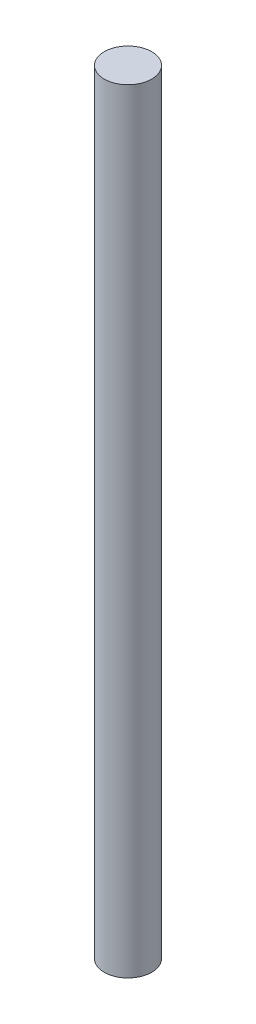
SolidWorks part; units mm, degrees
ref_plane "Front Plane" through (0, 0, 0) normal (0, 0, 1) x (1, 0, 0)
ref_plane "Top Plane" through (0, 0, 0) normal (0, 1, 0) x (1, 0, 0)
ref_plane "Right Plane" through (0, 0, 0) normal (1, 0, 0) x (0, 0, -1)
sketch "Sketch1" plane through (0, 0, 0) normal (0, 0, 1) x (1, 0, 0)
  line L0 (0, 0) -> (0, 220)
  point P6 (0, 220)
  dimension "D2" = 220
sketch "Sketch2" plane through (0, 0, 0) normal (0, 1, 0) x (1, 0, 0)
  circle A0 centre (0, 0) radius 6.75
  dimension "D1" = 13.5
sweep "Sweep1" add profiles "Sketch2" path "Sketch1"
